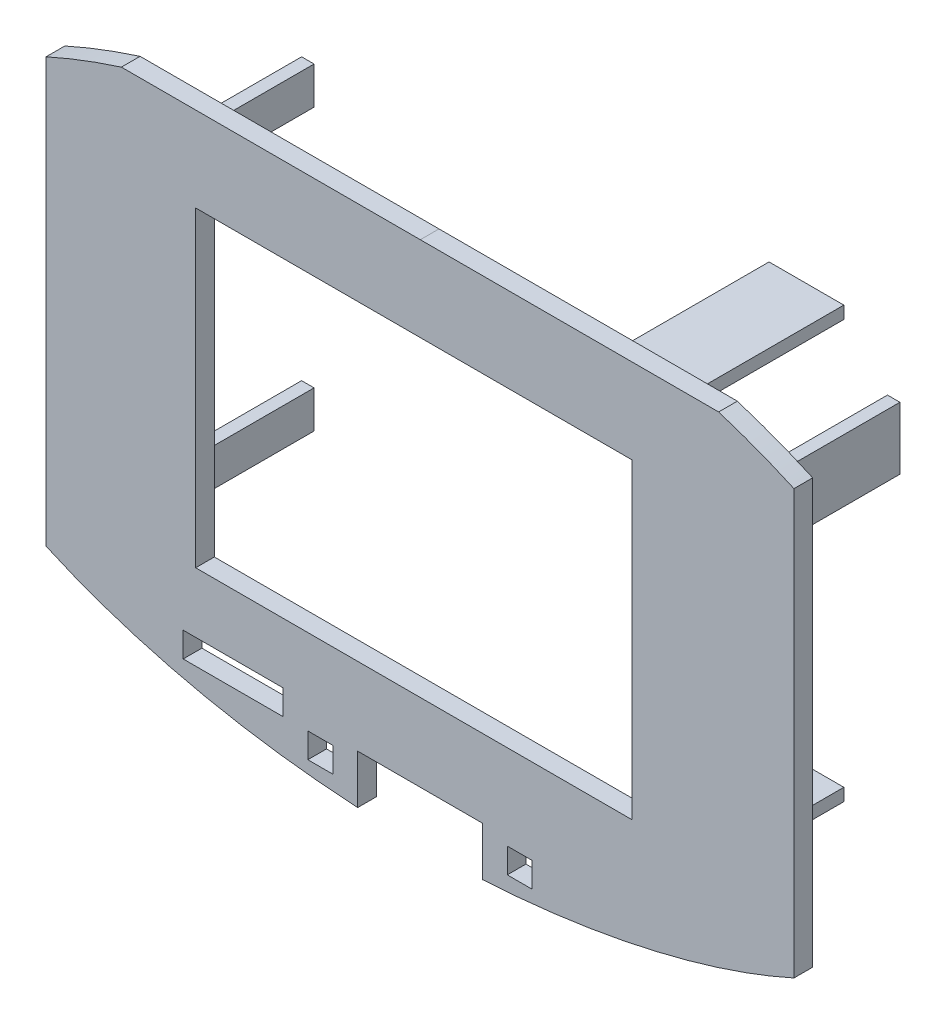
SolidWorks part; units mm, degrees
ref_plane "前视基准面" through (0, 0, 0) normal (0, 0, 1) x (1, 0, 0)
ref_plane "上视基准面" through (0, 0, 0) normal (0, 1, 0) x (1, 0, 0)
ref_plane "右视基准面" through (0, 0, 0) normal (1, 0, 0) x (0, 0, -1)
sketch "草图1" plane through (0, 0, 0) normal (0, 0, 1) x (1, 0, 0)
  line L0 (-60, 34) -> (-60, -34)
  line L1 (60, 34) -> (60, -34)
  ellipse E0 centre (0, 0) end of major axis (-90.0291, 0) minor radius 45.604 (-60, -34) -> (60, -34) ccw
  ellipse E1 centre (0, 0) end of major axis (-90.0291, 0) minor radius 45.604 (60, 34) -> (-60, 34) ccw
  point P10 (-60, -34)
  point P12 (-60, 42.9076)
  point P13 (-60, -42.9076)
  point P15 (-60, 34)
  dimension "D1" = 60
  dimension "D2" = 60
extrude "凸台-拉伸1" add sketch "草图1" along normal blind 3
sketch "草图3" plane through (0, 0, 0) normal (0, 0, -1) x (-1, 0, 0)
  line L0 (-39, -32.5) -> (-27, -32.5)
  line L1 (46, -19.5) -> (46, -25.5)
  line L2 (46, 25.5) -> (46, 19.5)
  line L3 (-39, -32.5) -> (-39, -34.5)
  line L4 (-39, 32.5) -> (-39, 34.5)
  line L5 (-39, 34.5) -> (-27, 34.5)
  line L6 (-27, 34.5) -> (-27, 32.5)
  line L7 (-39, -34.5) -> (-27, -34.5)
  line L8 (-27, -34.5) -> (-27, -32.5)
  line L9 (46, 25.5) -> (48, 25.5)
  line L10 (48, 25.5) -> (48, 19.5)
  line L11 (48, 19.5) -> (46, 19.5)
  line L12 (46, -19.5) -> (48, -19.5)
  line L13 (48, -19.5) -> (48, -25.5)
  line L14 (48, -25.5) -> (46, -25.5)
  line L15 (-46, 25.5) -> (-46, 15.5)
  line L16 (-46, 25.5) -> (-48, 25.5)
  line L17 (-48, 25.5) -> (-48, 15.5)
  line L18 (-48, 15.5) -> (-46, 15.5)
  line L19 (-39, 32.5) -> (-27, 32.5)
  dimension "D2" = 32.5
  dimension "D3" = 46
  dimension "D4" = 65
  dimension "D7" = 10
  dimension "D8" = 12
  dimension "D9" = 6
  dimension "D10" = 6
  dimension "D11" = 12
  dimension "D12" = 7
  dimension "D13" = 2
  dimension "D14" = 2
  dimension "D15" = 2
  dimension "D16" = 2
  dimension "D17" = 85
extrude "凸台-拉伸2" add sketch "草图3" along normal blind 26
sketch "草图4" plane through (0, 0, 0) normal (0, 0, -1) x (-1, 0, 0)
  line L0 (-10, -45.3218) -> (-10, -37.4795)
  line L1 (-10, -37.4795) -> (10, -37.4795)
  line L2 (10, -37.4795) -> (10, -45.3218)
  ellipse E0 centre (0, 0) end of major axis (90.0291, 0) minor radius 45.604 (-60, -34) -> (60, -34) ccw construction
  point P11 (0, -37.4795)
extrude "切除-拉伸5" cut sketch "草图4" against normal blind 3 and the other way through all flip side to cut
sketch "草图5" plane through (0, 0, 0) normal (0, 0, -1) x (-1, 0, 0)
  line L0 (-18, -38.6702) -> (-14, -38.6702)
  line L1 (-14, -38.6702) -> (-14, -42.6702)
  line L2 (-14, -42.6702) -> (-18, -42.6702)
  line L3 (-18, -42.6702) -> (-18, -38.6702)
  line L4 (-10, -37.4795) -> (-10, -45.3218) construction
  line L5 (10, -45.3218) -> (10, -37.4795) construction
  line L6 (22, -38.6702) -> (22, -34.6702)
  line L7 (22, -34.6702) -> (38, -34.6702)
  line L8 (18, -42.6702) -> (18, -38.6702)
  line L9 (14, -42.6702) -> (18, -42.6702)
  line L10 (14, -38.6702) -> (14, -42.6702)
  line L11 (18, -38.6702) -> (14, -38.6702)
  line L12 (38, -34.6702) -> (38, -38.6702)
  line L13 (38, -38.6702) -> (22, -38.6702)
  dimension "D1" = 4
  dimension "D2" = 4
  dimension "D3" = 4
extrude "切除-拉伸6" cut sketch "草图5" against normal blind 3
sketch "草图6" plane through (0, 0, 0) normal (0, 0, -1) x (-1, 0, 0)
  line L0 (-34, 25) -> (-34, -25)
  line L1 (-34, -25) -> (36, -25)
  line L2 (36, -25) -> (36, 25)
  line L3 (36, 25) -> (-34, 25)
  line L4 (46, 25.5) -> (46, 19.5) construction
  dimension "D1" = 10
  dimension "D2" = 70
  dimension "D3" = 50
extrude "切除-拉伸7" cut sketch "草图6" against normal blind 10
sketch "草图7" plane through (0, 0, 0) normal (0, 0, -1) x (-1, 0, 0)
  line L2 (-0.0475, 38.6089) -> (-47.9144, 38.6089)
  line L3 (-0.0475, 38.6089) -> (47.9144, 38.6089)
  ellipse E1 centre (0, 0) end of major axis (90.0291, 0) minor radius 45.604 (60, 34) -> (-60, 34) ccw construction
extrude "切除-拉伸10" cut sketch "草图7" against normal blind 3 and the other way through all
